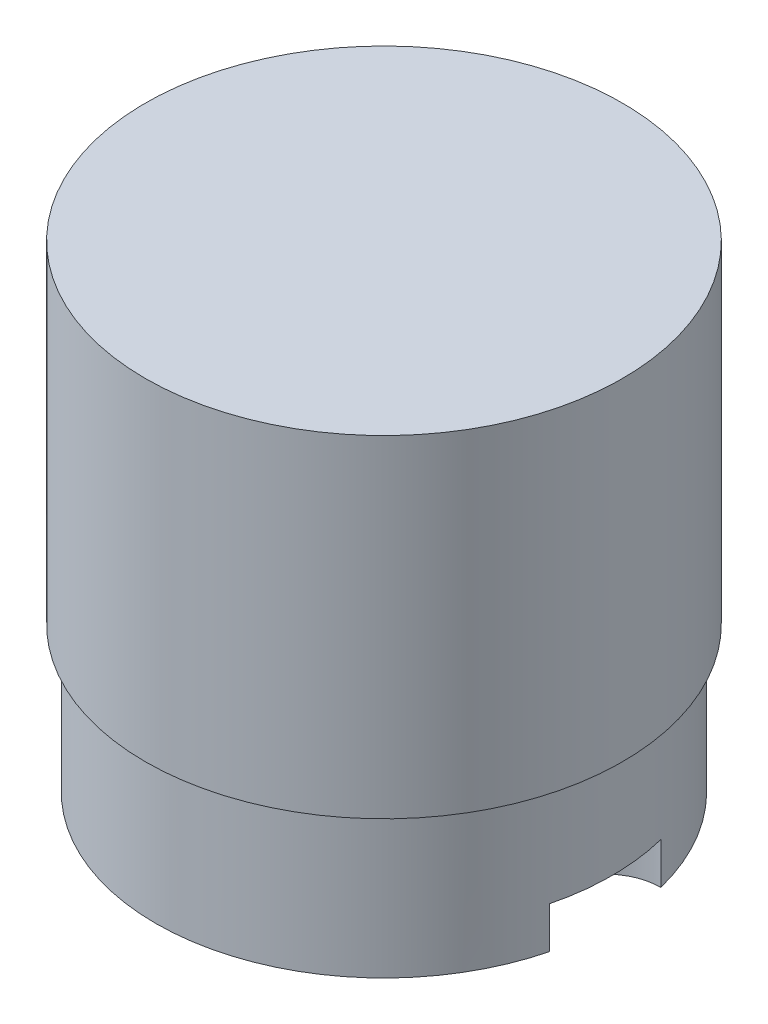
SolidWorks part; units mm, degrees
material "Nylon 101"
ref_plane "Front Plane" through (0, 0, 0) normal (0, 0, 1) x (1, 0, 0)
ref_plane "Top Plane" through (0, 0, 0) normal (0, 1, 0) x (1, 0, 0)
ref_plane "Right Plane" through (0, 0, 0) normal (1, 0, 0) x (0, 0, -1)
sketch "Sketch1" plane through (0, 0, 0) normal (1, 0, 0) x (0, 0, -1)
  line L0 (0, 13.5228) -> (0, -12.9382) construction
  line L1 (0, 5.75) -> (-5.75, 5.75)
  line L2 (-5.75, 5.75) -> (-5.75, -2.25)
  line L3 (-5.75, -2.25) -> (-5.5, -2.25)
  line L4 (-5.5, -2.25) -> (-5.5, -5.75)
  line L5 (-5.5, -5.75) -> (0, -5.75)
  line L6 (-0.9312, 0) -> (1.3508, 0) construction
  line L7 (0, 5.75) -> (0, -5.75)
  dimension "D1" = 11.5
  dimension "D2" = 8
  dimension "D3" = 11
  dimension "D4" = 3.5
  dimension "D5" = 11.5
revolve "Revolve1" add sketch "Sketch1" angle 360 about L7
sketch "Sketch2" plane through (0, -5.75, 0) normal (0, -1, 0) x (1, 0, 0)
  line L0 (0, 5.7805) -> (0, -5.7527) construction
  line L1 (-6.8088, 0) -> (8.9487, 0) construction
  line L2 (-0.175, -1.25) -> (0.175, -1.25)
  line L3 (2.625, 2.5) -> (2.975, 2.5)
  line L4 (2.625, 2.5) -> (2.625, 1.25)
  line L5 (2.625, 1.25) -> (2.975, 1.25)
  line L6 (2.975, 2.5) -> (2.975, 1.25)
  line L7 (2.625, 2.5) -> (2.975, 1.25) construction
  line L8 (2.625, 1.25) -> (2.975, 2.5) construction
  line L9 (-0.175, 2.5) -> (0.175, 2.5)
  line L10 (-0.175, 2.5) -> (-0.175, 1.25)
  line L11 (-0.175, 1.25) -> (0.175, 1.25)
  line L12 (0.175, 2.5) -> (0.175, 1.25)
  line L13 (-0.175, 2.5) -> (0.175, 1.25) construction
  line L14 (-0.175, 1.25) -> (0.175, 2.5) construction
  line L15 (0.175, -2.5) -> (0.175, -1.25)
  line L16 (-0.175, -2.5) -> (0.175, -2.5)
  line L17 (-0.175, -2.5) -> (-0.175, -1.25)
  line L18 (2.625, -1.25) -> (2.975, -1.25)
  line L19 (2.975, -2.5) -> (2.975, -1.25)
  line L20 (2.625, -2.5) -> (2.975, -2.5)
  line L21 (2.625, -2.5) -> (2.625, -1.25)
  line L22 (-2.625, -2.5) -> (-2.625, -1.25)
  line L23 (-2.625, -2.5) -> (-2.975, -2.5)
  line L24 (-2.975, -2.5) -> (-2.975, -1.25)
  line L25 (-2.625, -1.25) -> (-2.975, -1.25)
  line L26 (-2.625, 1.25) -> (-2.975, 1.25)
  line L27 (-2.975, 2.5) -> (-2.975, 1.25)
  line L28 (-2.625, 2.5) -> (-2.975, 2.5)
  line L29 (-2.625, 2.5) -> (-2.625, 1.25)
  line L30 (5.3343, 4.2339) -> (5.3343, -1.6097) construction
  arc A9 (5.3343, 1.34) -> (5.3343, -1.34) centre (5.3343, 0) ccw
  circle A12 centre (0, 0) radius 5.5 construction
  circle A13 centre (0, 0) radius 5.5 construction
  arc A14 (5.3343, -1.34) -> (5.3343, 1.34) centre (0, 0) ccw
  arc A15 (-5.3343, 1.34) -> (-5.3343, -1.34) centre (-5.3343, 0) cw
  arc A16 (-5.3343, -1.34) -> (-5.3343, 1.34) centre (0, 0) cw
  point P8 (0, 1.875)
  point P13 (2.8, 1.875)
  point P44 (0, 0)
  point P46 (1.4554, 0.0139)
  dimension "D1" = 0.35
  dimension "D6" = 2.68
  dimension "D2" = 1.25
  dimension "D3" = 1.25
  dimension "D4" = 0.35
  dimension "D5" = 2.45
extrude "Cut-Extrude1" cut sketch "Sketch2" against normal blind 1
sketch "Sketch3" plane through (0, -5.75, 0) normal (0, -1, 0) x (1, 0, 0)
  line L0 (0, 5.6555) -> (0, -6.1001) construction
  line L1 (-6.2113, 0) -> (7.1562, 0) construction
  line L2 (2, 0.9595) -> (2, -1.0515) construction
  line L3 (1.25, -0.125) -> (1.875, -0.125)
  line L4 (1.25, -0.125) -> (1.25, 0.125)
  line L5 (1.25, 0.125) -> (1.875, 0.125)
  line L6 (2.75, -0.125) -> (2.75, 0.125)
  line L7 (1.25, -0.125) -> (2.75, 0.125) construction
  line L8 (1.25, 0.125) -> (2.75, -0.125) construction
  line L9 (-1.25, 0.125) -> (-2.75, 0.125)
  line L10 (-2.75, -0.125) -> (-2.75, 0.125)
  line L11 (-1.25, -0.125) -> (-2.75, -0.125)
  line L12 (-1.25, -0.125) -> (-1.25, 0.125)
  line L13 (1.9792, 0.125) -> (2.0208, 0.125) construction
  line L14 (1.875, 0.75) -> (2.125, 0.75)
  line L15 (1.875, 0.75) -> (1.875, 0.125)
  line L16 (1.875, -0.75) -> (2.125, -0.75)
  line L17 (2.125, 0.75) -> (2.125, 0.125)
  line L18 (1.875, 0.75) -> (2.125, -0.75) construction
  line L19 (1.875, -0.75) -> (2.125, 0.75) construction
  line L20 (1.875, 0.0208) -> (1.875, -0.0208) construction
  line L21 (1.875, -0.125) -> (1.875, -0.75)
  line L22 (1.9792, -0.125) -> (2.0208, -0.125) construction
  line L23 (2.125, -0.125) -> (2.75, -0.125)
  line L24 (2.125, -0.125) -> (2.125, -0.75)
  line L25 (2.125, 0.125) -> (2.75, 0.125)
  line L26 (2.125, 0.0208) -> (2.125, -0.0208) construction
  point P5 (2, 0)
  point P16 (2, 0)
  dimension "D1" = 0.25
  dimension "D2" = 1.5
  dimension "D3" = 2
  dimension "D4" = 1.5
  dimension "D5" = 0.25
extrude "Boss-Extrude1" add sketch "Sketch3" along normal blind 0.25
